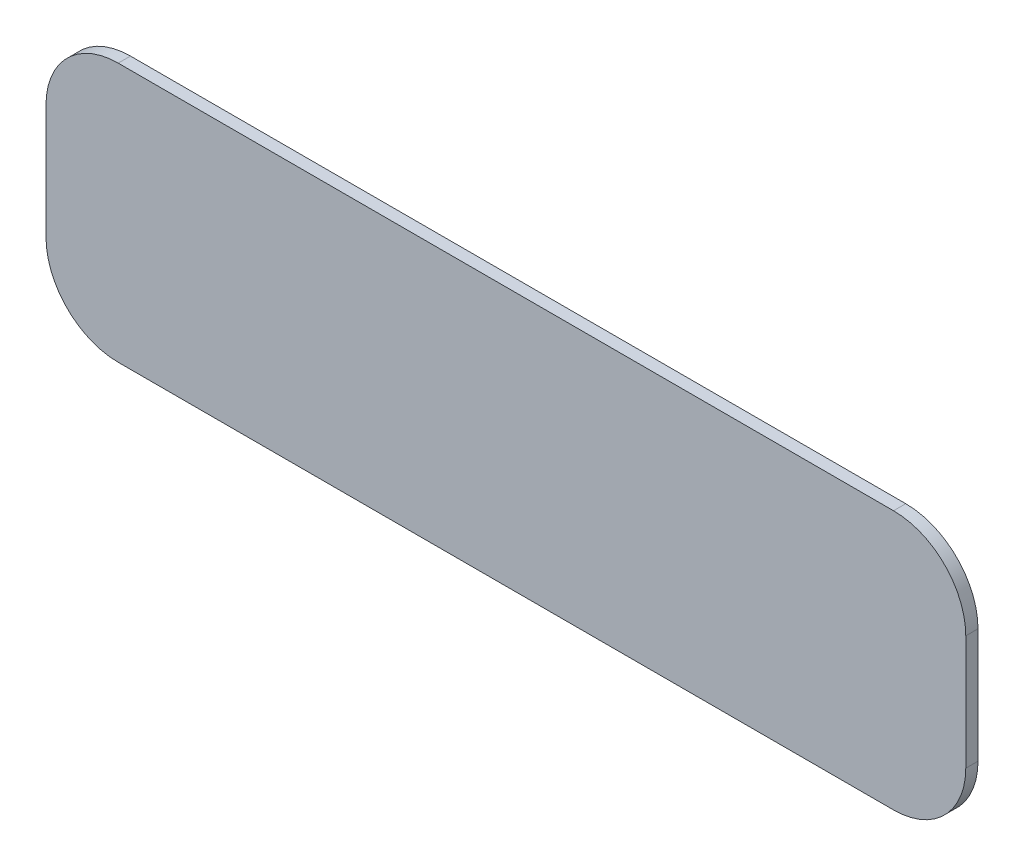
SolidWorks part; units mm, degrees
ref_plane "Plan de face" through (0, 0, 0) normal (0, 0, 1) x (1, 0, 0)
ref_plane "Plan de dessus" through (0, 0, 0) normal (0, 1, 0) x (1, 0, 0)
ref_plane "Plan de droite" through (0, 0, 0) normal (1, 0, 0) x (0, 0, -1)
sketch "Esquisse1" plane through (0, 0, 0) normal (0, 0, 1) x (1, 0, 0)
  line L1 (-95, -31.75) -> (95, -31.75)
  line L2 (-112.7, -14.05) -> (-112.7, 14.05)
  line L3 (-95, 31.75) -> (95, 31.75)
  line L4 (112.7, -14.05) -> (112.7, 14.05)
  line L5 (-112.7, -31.75) -> (112.7, 31.75) construction
  line L6 (-112.7, 31.75) -> (112.7, -31.75) construction
  arc A0 (95, 31.75) -> (112.7, 14.05) centre (95, 14.05) cw
  arc A1 (95, -31.75) -> (112.7, -14.05) centre (95, -14.05) ccw
  arc A2 (-95, -31.75) -> (-112.7, -14.05) centre (-95, -14.05) cw
  arc A3 (-112.7, 14.05) -> (-95, 31.75) centre (-95, 14.05) cw
  point P0 (0, 0)
  point P18 (0, 0)
  point P19 (0, 0)
  dimension "D3" = 17.7
  dimension "D1" = 225.4
  dimension "D2" = 63.5
extrude "Boss.-Extru.1" add sketch "Esquisse1" along normal blind 3
